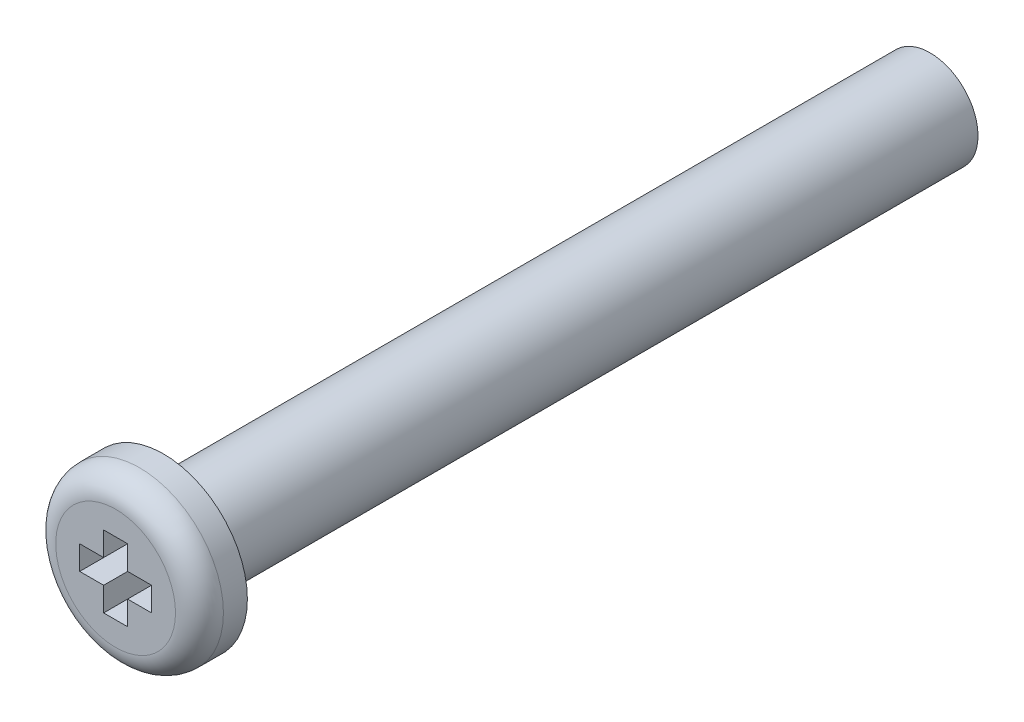
SolidWorks part; units mm, degrees
ref_plane "前视基准面" through (0, 0, 0) normal (0, 0, 1) x (1, 0, 0)
ref_plane "上视基准面" through (0, 0, 0) normal (0, 1, 0) x (1, 0, 0)
ref_plane "右视基准面" through (0, 0, 0) normal (1, 0, 0) x (0, 0, -1)
sketch "草图1" plane through (0, 0, 0) normal (0, 0, 1) x (1, 0, 0)
  circle A0 centre (0, 0) radius 2
extrude "凸台-拉伸1" add sketch "草图1" along normal blind 32
sketch "草图2" plane through (0, 0, 32) normal (0, 0, 1) x (1, 0, 0)
  circle A0 centre (0, 0) radius 3.5
extrude "凸台-拉伸2" add sketch "草图2" along normal blind 2
fillet "圆角1" radius 1 1 edges at (3.5, 0, 34)
sketch "草图3" plane through (0, 0, 34) normal (0, 0, 1) x (1, 0, 0)
  line L2 (0, 1.5) -> (0.5, 1.5)
  line L3 (0, 1.5) -> (-0.5, 1.5)
  line L4 (0.5, 1.5) -> (0.5, 0.5)
  line L5 (0.5, 0.5) -> (1.5, 0.5)
  line L6 (1.5, 0.5) -> (1.5, -0.5)
  line L7 (1.5, -0.5) -> (0.5, -0.5)
  line L8 (0.5, -0.5) -> (0.5, -1.5)
  line L9 (0.5, -1.5) -> (-0.5, -1.5)
  line L10 (-0.5, -1.5) -> (-0.5, -0.5)
  line L11 (-0.5, -0.5) -> (-1.5, -0.5)
  line L12 (-1.5, -0.5) -> (-1.5, 0.5)
  line L13 (-1.5, 0.5) -> (-0.5, 0.5)
  line L14 (-0.5, 0.5) -> (-0.5, 1.5)
extrude "切除-拉伸1" cut sketch "草图3" against normal blind 2
